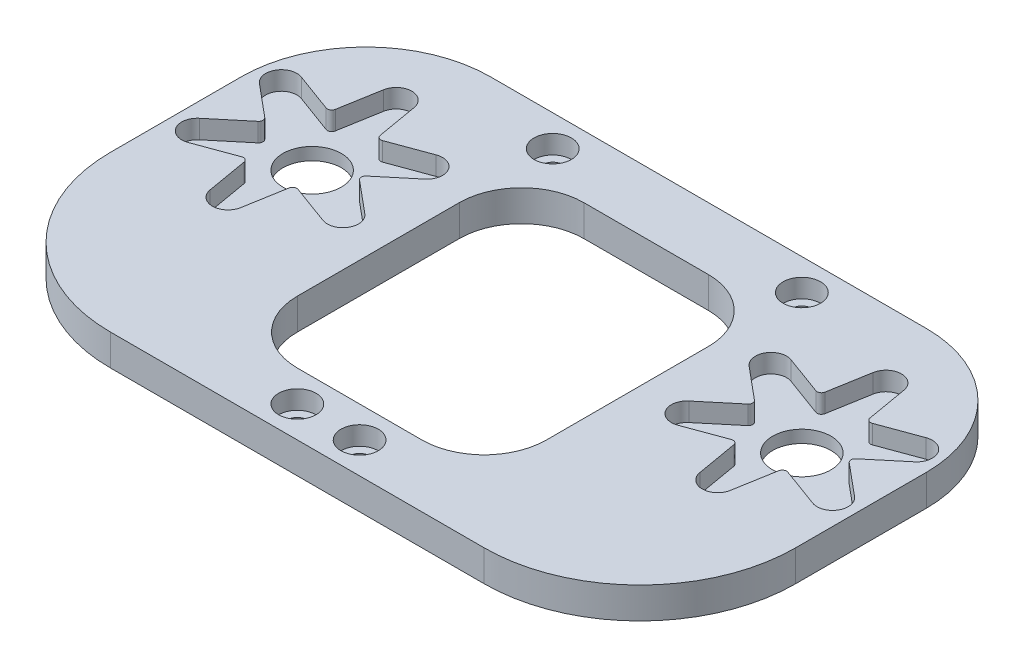
SolidWorks part; units mm, degrees
ref_plane "Alzado" through (0, 0, 0) normal (0, 0, 1) x (1, 0, 0)
ref_plane "Planta" through (0, 0, 0) normal (0, 1, 0) x (1, 0, 0)
ref_plane "Vista lateral" through (0, 0, 0) normal (1, 0, 0) x (0, 0, -1)
sketch "Croquis1" plane through (0, 0, 0) normal (0, 1, 0) x (1, 0, 0)
  line L0 (0, -36.3) -> (0, 36.3) construction
  line L1 (-30, -33) -> (30, -33)
  line L2 (-55, -8) -> (-55, 13)
  line L3 (-35, 33) -> (35, 33)
  line L4 (55, -8) -> (55, 13)
  line L5 (-55, -33) -> (55, 33) construction
  line L6 (-55, 33) -> (55, -33) construction
  line L7 (-10, -23) -> (10, -23)
  line L8 (-20, -13) -> (-20, 13)
  line L9 (-10, 23) -> (10, 23)
  line L10 (20, -13) -> (20, 13)
  line L11 (-20, -23) -> (20, 23) construction
  line L12 (-20, 23) -> (20, -23) construction
  line L13 (39.3125, 4) -> (39.3125, -33) construction
  line L14 (44, 8.6875) -> (55, 8.6875) construction
  arc A0 (55, 13) -> (35, 33) centre (35, 13) ccw
  arc A1 (-35, 33) -> (-55, 13) centre (-35, 13) ccw
  arc A2 (55, -8) -> (30, -33) centre (30, -8) cw
  arc A3 (-55, -8) -> (-30, -33) centre (-30, -8) ccw
  arc A4 (-10, -23) -> (-20, -13) centre (-10, -13) cw
  arc A5 (10, -23) -> (20, -13) centre (10, -13) ccw
  arc A6 (20, 13) -> (10, 23) centre (10, 13) ccw
  arc A7 (-10, 23) -> (-20, 13) centre (-10, 13) ccw
  circle A8 centre (5, -28) radius 1.6
  circle A9 centre (20, 28) radius 1.6
  circle A10 centre (39.3125, 8.6875) radius 4.6875
  circle A11 centre (-5, -28) radius 1.6
  circle A12 centre (-39.3125, 8.6875) radius 4.6875
  circle A13 centre (-20, 28) radius 1.6
  point P0 (0, 0)
  point P18 (0, 0)
  dimension "D3" = 20
  dimension "D4" = 25
  dimension "D7" = 10
  dimension "D8" = 3.2
  dimension "D11" = 3.2
  dimension "D14" = 9.375
  dimension "D1" = 110
  dimension "D2" = 66
  dimension "D5" = 46
  dimension "D6" = 40
  dimension "D9" = 5
  dimension "D10" = 5
  dimension "D12" = 5
  dimension "D13" = 20
  dimension "D15" = 37
  dimension "D16" = 11
extrude "Saliente-Extruir1" add sketch "Croquis1" along normal blind 5
sketch "Croquis2" plane through (0, 5, 0) normal (0, 1, 0) x (1, 0, 0)
  line L0 (39.3125, 8.6875) -> (39.3125, 22.1875) construction
  line L1 (39.3125, 8.6875) -> (35.5625, 15.1827) construction
  line L2 (35.7057, 16.0099) -> (36.8491, 22.614)
  line L3 (42.9193, 16.0099) -> (41.7759, 22.614)
  line L4 (39.3125, 8.6875) -> (43.0625, 15.1827) construction
  line L5 (43.8505, 15.4723) -> (50.1415, 17.7841)
  line L6 (47.4573, 9.2251) -> (52.6049, 13.5174)
  line L7 (47.4573, 8.1499) -> (52.6049, 3.8576)
  line L8 (43.8505, 1.9027) -> (50.1415, -0.4091)
  line L9 (42.9193, 1.3651) -> (41.7759, -5.239)
  line L10 (35.7057, 1.3651) -> (36.8491, -5.239)
  line L11 (34.7745, 1.9027) -> (28.4835, -0.4091)
  line L12 (31.1677, 8.1499) -> (26.0201, 3.8576)
  line L13 (31.1677, 9.2251) -> (26.0201, 13.5174)
  line L14 (34.7745, 15.4723) -> (28.4835, 17.7841)
  line L15 (0, -2.75) -> (0, 2.75) construction
  line L16 (-34.7745, 15.4723) -> (-28.4835, 17.7841)
  line L17 (-31.1677, 9.2251) -> (-26.0201, 13.5174)
  line L18 (-31.1677, 8.1499) -> (-26.0201, 3.8576)
  line L19 (-34.7745, 1.9027) -> (-28.4835, -0.4091)
  line L20 (-35.7057, 1.3651) -> (-36.8491, -5.239)
  line L21 (-42.9193, 1.3651) -> (-41.7759, -5.239)
  line L22 (-43.8505, 1.9027) -> (-50.1415, -0.4091)
  line L23 (-47.4573, 8.1499) -> (-52.6049, 3.8576)
  line L24 (-47.4573, 9.2251) -> (-52.6049, 13.5174)
  line L25 (-43.8505, 15.4723) -> (-50.1415, 17.7841)
  line L26 (-42.9193, 16.0099) -> (-41.7759, 22.614)
  line L27 (-35.7057, 16.0099) -> (-36.8491, 22.614)
  circle A0 centre (39.3125, 8.6875) radius 4.6875 construction
  circle A1 centre (39.3125, 8.6875) radius 4.6875
  circle A2 centre (39.3125, 8.6875) radius 7.5 construction
  arc A3 (41.7759, 22.614) -> (36.8491, 22.614) centre (39.3125, 22.1875) ccw
  arc A4 (52.6049, 13.5174) -> (50.1415, 17.7841) centre (51.0038, 15.4375) ccw
  arc A5 (50.1415, -0.4091) -> (52.6049, 3.8576) centre (51.0038, 1.9375) ccw
  arc A6 (36.8491, -5.239) -> (41.7759, -5.239) centre (39.3125, -4.8125) ccw
  arc A7 (26.0201, 3.8576) -> (28.4835, -0.4091) centre (27.6212, 1.9375) ccw
  arc A8 (28.4835, 17.7841) -> (26.0201, 13.5174) centre (27.6212, 15.4375) ccw
  arc A9 (35.7057, 16.0099) -> (34.7745, 15.4723) centre (35.016, 16.1293) cw
  arc A10 (31.1677, 8.1499) -> (31.1677, 9.2251) centre (30.7195, 8.6875) ccw
  arc A11 (35.7057, 1.3651) -> (34.7745, 1.9027) centre (35.016, 1.2457) ccw
  arc A12 (43.8505, 1.9027) -> (42.9193, 1.3651) centre (43.609, 1.2457) ccw
  arc A13 (47.4573, 9.2251) -> (47.4573, 8.1499) centre (47.9055, 8.6875) ccw
  arc A14 (42.9193, 16.0099) -> (43.8505, 15.4723) centre (43.609, 16.1293) ccw
  circle A15 centre (20, 28) radius 1.6 construction
  circle A16 centre (20, 28) radius 1.6
  circle A17 centre (20, 28) radius 3
  circle A18 centre (5, -28) radius 1.6 construction
  circle A19 centre (5, -28) radius 1.6
  circle A20 centre (5, -28) radius 3
  circle A21 centre (-5, -28) radius 3
  arc A22 (-28.4835, 17.7841) -> (-26.0201, 13.5174) centre (-27.6212, 15.4375) cw
  arc A23 (-31.1677, 8.1499) -> (-31.1677, 9.2251) centre (-30.7195, 8.6875) cw
  arc A24 (-26.0201, 3.8576) -> (-28.4835, -0.4091) centre (-27.6212, 1.9375) cw
  arc A25 (-35.7057, 1.3651) -> (-34.7745, 1.9027) centre (-35.016, 1.2457) cw
  arc A26 (-36.8491, -5.239) -> (-41.7759, -5.239) centre (-39.3125, -4.8125) cw
  arc A27 (-43.8505, 1.9027) -> (-42.9193, 1.3651) centre (-43.609, 1.2457) cw
  arc A28 (-50.1415, -0.4091) -> (-52.6049, 3.8576) centre (-51.0038, 1.9375) cw
  arc A29 (-47.4573, 9.2251) -> (-47.4573, 8.1499) centre (-47.9055, 8.6875) cw
  arc A30 (-52.6049, 13.5174) -> (-50.1415, 17.7841) centre (-51.0038, 15.4375) cw
  arc A31 (-42.9193, 16.0099) -> (-43.8505, 15.4723) centre (-43.609, 16.1293) cw
  arc A32 (-41.7759, 22.614) -> (-36.8491, 22.614) centre (-39.3125, 22.1875) cw
  arc A33 (-35.7057, 16.0099) -> (-34.7745, 15.4723) centre (-35.016, 16.1293) ccw
  circle A34 centre (-20, 28) radius 3
  point P38 (39.3125, 8.6875)
  dimension "D1" = 15
  dimension "D3" = 2.5
  dimension "D6" = 0.7
  dimension "D7" = 6
  dimension "D2" = 30
  dimension "D4" = 13.5
  dimension "D5" = 6
extrude "Cortar-Extruir1" cut sketch "Croquis2" against normal blind 3
